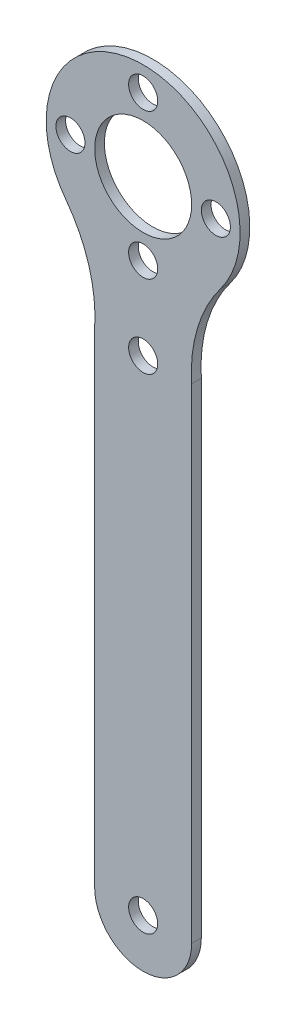
SolidWorks part; units mm, degrees
ref_plane "前视基准面" through (0, 0, 0) normal (0, 0, 1) x (1, 0, 0)
ref_plane "上视基准面" through (0, 0, 0) normal (0, 1, 0) x (1, 0, 0)
ref_plane "右视基准面" through (0, 0, 0) normal (1, 0, 0) x (0, 0, -1)
sketch "草图1" plane through (0, 0, 0) normal (0, 0, 1) x (1, 0, 0)
  line L0 (0, -25) -> (0, 25) construction
  line L1 (-5, -25) -> (-5, 25)
  line L2 (5, -25) -> (5, 25)
  arc A0 (-5, -25) -> (5, -25) centre (0, -25) ccw
  arc A1 (5, 25) -> (-5, 25) centre (0, 25) ccw
  circle A2 centre (0, 25) radius 1.5
  circle A3 centre (0, -25) radius 1.5
  circle A4 centre (0, 41) radius 10
  circle A5 centre (0, 41) radius 5
  circle A6 centre (0, 41) radius 7.5 construction
  circle A7 centre (0, 48.5) radius 1.5
  circle A8 centre (7.5, 41) radius 1.5
  circle A9 centre (0, 33.5) radius 1.5
  circle A10 centre (-7.5, 41) radius 1.5
  arc A11 (-5, 25) -> (-7.9877, 34.9837) centre (-19.9693, 25.9592) ccw
  arc A12 (5, 25) -> (7.9877, 34.9837) centre (19.9693, 25.9592) cw
  point P2 (0, 0)
  point P27 (0, 41)
  point P31 (0, 0)
  dimension "D3" = 3
  dimension "D4" = 3
  dimension "D5" = 20
  dimension "D7" = 10
  dimension "D8" = 15
  dimension "D9" = 3
  dimension "D11" = 15
  dimension "D12" = 15
  dimension "D1" = 50
  dimension "D2" = 10
  dimension "D6" = 16
  dimension "D10" = 4
extrude "凸台-拉伸1" add sketch "草图1" along normal blind 1 contours A4 A10 A9 A8 A7 A5 | L2 A1 L1 A0 A3 A2 | A1 A12 A4 | A11 A1 A4
